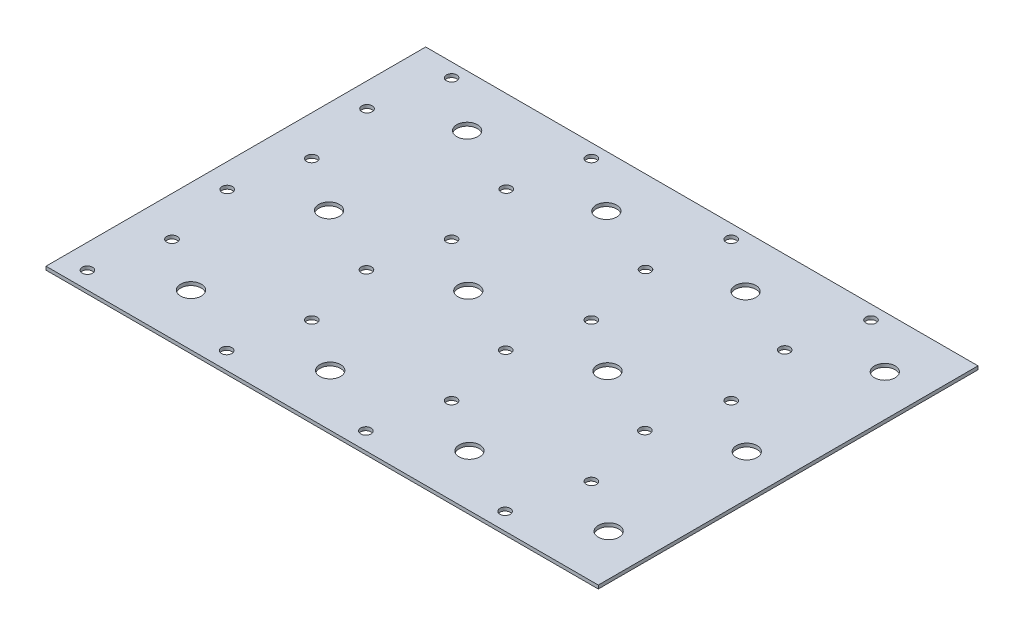
SolidWorks part; units mm, degrees
ref_plane "Front Plane" through (0, 0, 0) normal (0, 0, 1) x (1, 0, 0)
ref_plane "Top Plane" through (0, 0, 0) normal (0, 1, 0) x (1, 0, 0)
ref_plane "Right Plane" through (0, 0, 0) normal (1, 0, 0) x (0, 0, -1)
sketch "Sketch1" plane through (0, 0, 0) normal (0, 1, 0) x (1, 0, 0)
  line L1 (-80, -55) -> (80, -55)
  line L2 (-80, -55) -> (-80, 55)
  line L3 (-80, 55) -> (80, 55)
  line L4 (80, -55) -> (80, 55)
  line L5 (-80, -55) -> (80, 55) construction
  line L6 (-80, 55) -> (80, -55) construction
  point P0 (0, 0)
  dimension "D1" = 160
  dimension "D2" = 110
extrude "Boss-Extrude1" add sketch "Sketch1" along normal blind 1
sketch "Sketch2" plane through (0, 1, 0) normal (0, 1, 0) x (1, 0, 0)
  line L0 (-80, 55) -> (-80, -55) construction
  line L1 (80, 55) -> (-80, 55) construction
  line L2 (80, -55) -> (80, 55) construction
  line L3 (-80, -55) -> (80, -55) construction
  circle A0 centre (-53, 40) radius 3
  circle A1 centre (-12.6667, 40) radius 3
  circle A2 centre (27.6667, 40) radius 3
  circle A3 centre (68, 40) radius 3
  circle A4 centre (-12.6667, 0) radius 3
  circle A5 centre (27.6667, 0) radius 3
  circle A6 centre (68, 0) radius 3
  circle A7 centre (-12.6667, -40) radius 3
  circle A8 centre (27.6667, -40) radius 3
  circle A9 centre (68, -40) radius 3
  circle A10 centre (-53, 0) radius 3
  circle A11 centre (-53, -40) radius 3
  circle A12 centre (-68.5, 51) radius 1.5
  circle A13 centre (-28, 51) radius 1.5
  circle A14 centre (12.5, 51) radius 1.5
  circle A15 centre (53, 51) radius 1.5
  circle A16 centre (-28, 10.5) radius 1.5
  circle A17 centre (12.5, 10.5) radius 1.5
  circle A18 centre (53, 10.5) radius 1.5
  circle A19 centre (-28, -30) radius 1.5
  circle A20 centre (12.5, -30) radius 1.5
  circle A21 centre (53, -30) radius 1.5
  circle A22 centre (-68.5, 10.5) radius 1.5
  circle A23 centre (-68.5, -30) radius 1.5
  circle A24 centre (-73, 31) radius 1.5
  circle A25 centre (-32.6667, 31) radius 1.5
  circle A26 centre (7.6667, 31) radius 1.5
  circle A27 centre (48, 31) radius 1.5
  circle A28 centre (-32.6667, -9.5) radius 1.5
  circle A29 centre (7.6667, -9.5) radius 1.5
  circle A30 centre (48, -9.5) radius 1.5
  circle A31 centre (-32.6667, -50) radius 1.5
  circle A32 centre (7.6667, -50) radius 1.5
  circle A33 centre (48, -50) radius 1.5
  circle A34 centre (-73, -9.5) radius 1.5
  circle A35 centre (-73, -50) radius 1.5
  point P32 (0, 0)
  dimension "D1" = 6
  dimension "D8" = 3
  dimension "D15" = 3
  dimension "D2" = 27
  dimension "D3" = 15
  dimension "D6" = 12
  dimension "D7" = 15
  dimension "D9" = 11.5
  dimension "D12" = 27
  dimension "D13" = 4
  dimension "D14" = 25
  dimension "D16" = 24
  dimension "D17" = 7
  dimension "D20" = 32
  dimension "D21" = 5
  dimension "D4" = 4
  dimension "D5" = 3
  dimension "D10" = 4
  dimension "D11" = 3
  dimension "D18" = 4
  dimension "D19" = 3
extrude "Cut-Extrude1" cut sketch "Sketch2" against normal up to next (1 mm away)
